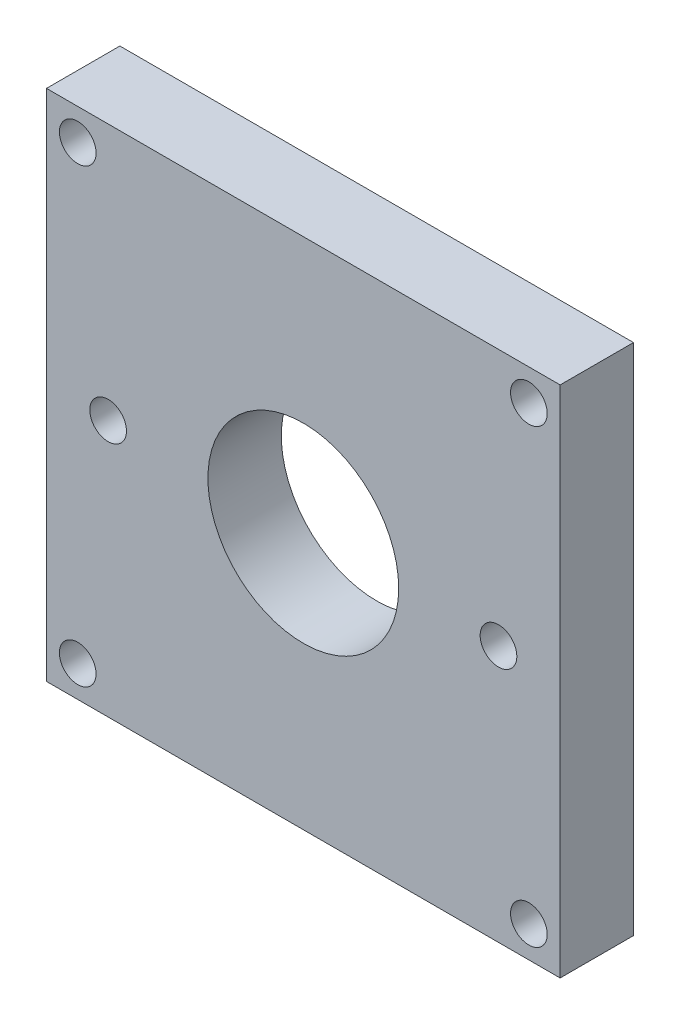
SolidWorks part; units mm, degrees
ref_plane "Alzado" through (0, 0, 0) normal (0, 0, 1) x (1, 0, 0)
ref_plane "Planta" through (0, 0, 0) normal (0, 1, 0) x (1, 0, 0)
ref_plane "Vista lateral" through (0, 0, 0) normal (1, 0, 0) x (0, 0, -1)
sketch "Croquis1" plane through (0, 0, 0) normal (0, 0, 1) x (1, 0, 0)
  line L0 (-17.5, 17.5) -> (-17.5, 13.25) construction
  line L1 (17.5, -17.5) -> (-17.5, -17.5)
  line L2 (17.5, -17.5) -> (17.5, 17.5)
  line L3 (17.5, 17.5) -> (-17.5, 17.5)
  line L4 (-17.5, -17.5) -> (-17.5, 17.5)
  line L5 (17.5, -17.5) -> (-17.5, 17.5) construction
  line L6 (17.5, 17.5) -> (-17.5, -17.5) construction
  line L7 (-17.5, 13.25) -> (-15.37, 13.25) construction
  line L8 (-15.37, 13.25) -> (-15.37, 15.37) construction
  line L9 (17.5, 13.25) -> (15.37, 13.25) construction
  line L10 (15.37, 13.25) -> (15.37, 15.37) construction
  line L11 (15.37, -17.5) -> (15.37, -15.37) construction
  line L12 (-17.5, -15.37) -> (-15.37, -15.37) construction
  line L13 (-13.3, 0) -> (13.3, 0)
  circle A0 centre (-15.37, 15.37) radius 1.25
  circle A1 centre (15.37, 15.37) radius 1.25
  circle A2 centre (15.37, -15.37) radius 1.25
  circle A3 centre (-15.37, -15.37) radius 1.25
  circle A4 centre (0, 0) radius 6.5
  circle A5 centre (13.3, 0) radius 1.25
  circle A6 centre (-13.3, 0) radius 1.25
  point P0 (0, 0)
  point P24 (0, 0)
  dimension "D5" = 2.5
  dimension "D8" = 2.5
  dimension "D10" = 2.5
  dimension "D12" = 2.5
  dimension "D13" = 13
  dimension "D15" = 2.5
  dimension "D16" = 1.25
  dimension "D1" = 35
  dimension "D2" = 4.25
  dimension "D3" = 2.13
  dimension "D4" = 2.12
  dimension "D6" = 2.13
  dimension "D7" = 2.12
  dimension "D9" = 2.13
  dimension "D11" = 2.13
  dimension "D14" = 13.3
extrude "Saliente-Extruir1" add sketch "Croquis1" along normal blind 5
